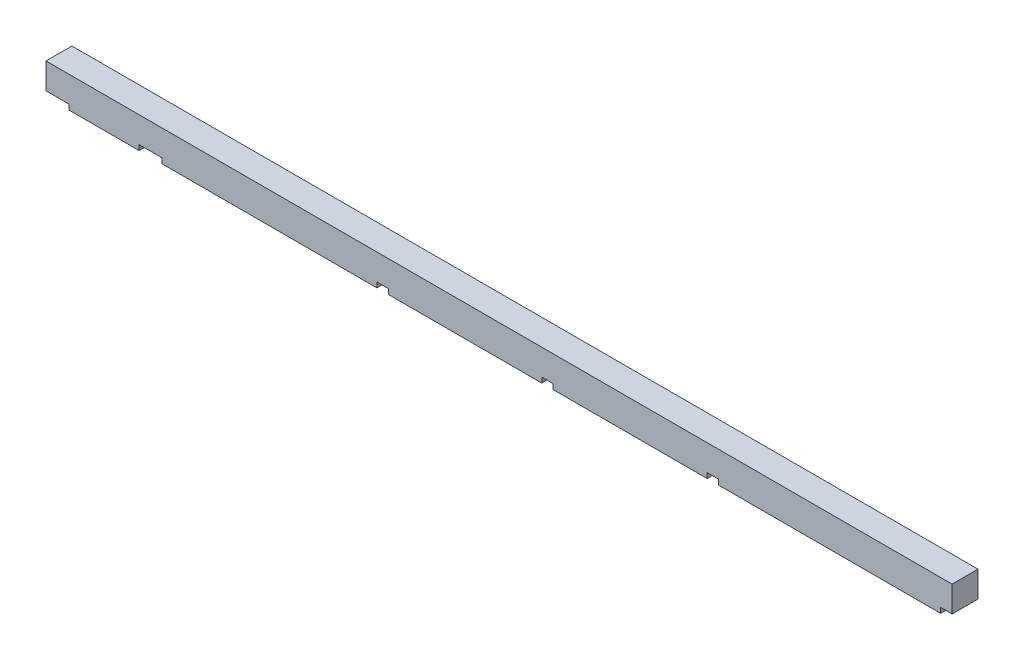
SolidWorks part; units mm, degrees
ref_plane "前视基准面" through (0, 0, 0) normal (0, 0, 1) x (1, 0, 0)
ref_plane "上视基准面" through (0, 0, 0) normal (0, 1, 0) x (1, 0, 0)
ref_plane "右视基准面" through (0, 0, 0) normal (1, 0, 0) x (0, 0, -1)
sketch "Model" plane through (0, 0, 0) normal (0, 0, 1) x (1, 0, 0)
  line L0 (67.2368, 3.6392) -> (69.4368, 3.6392)
  line L1 (69.4368, 2.6392) -> (99.0834, 2.6392)
  line L2 (101.2834, 2.6392) -> (131.0367, 2.6392)
  line L3 (131.0367, 2.6392) -> (131.0367, 3.6234)
  line L4 (131.0367, 3.6234) -> (133.236, 3.6392)
  line L5 (133.236, 3.6392) -> (133.236, 2.6392)
  line L6 (133.236, 2.6392) -> (176.136, 2.6392)
  line L7 (176.136, 2.6392) -> (176.136, 3.6392)
  line L8 (176.136, 3.6392) -> (178.336, 3.6392)
  line L9 (178.336, 3.6392) -> (178.336, 8.6392)
  line L10 (178.336, 8.6392) -> (50.336, 8.6392)
  line L11 (50.336, 8.6392) -> (3.336, 8.6392)
  line L12 (3.336, 8.6392) -> (3.336, 3.6392)
  line L13 (3.336, 3.6392) -> (7.736, 3.6392)
  line L14 (7.736, 3.6392) -> (7.736, 2.6392)
  line L15 (7.736, 2.6392) -> (21.3082, 2.6392)
  line L16 (69.4368, 3.6392) -> (69.4368, 2.6392)
  line L17 (101.2834, 2.6392) -> (101.2834, 3.6392)
  line L18 (101.2834, 3.6392) -> (99.0834, 3.6392)
  line L19 (99.0834, 3.6392) -> (99.0834, 2.6392)
  line L20 (67.2368, 3.6392) -> (67.2368, 2.6392)
  line L21 (21.3082, 2.6392) -> (21.3082, 3.6392)
  line L22 (21.3082, 3.6392) -> (25.7082, 3.6392)
  line L23 (25.7082, 3.6392) -> (25.7082, 2.6392)
  line L24 (25.7082, 2.6392) -> (67.2368, 2.6392)
extrude "凸台-拉伸1" add sketch "Model" along normal blind 5
